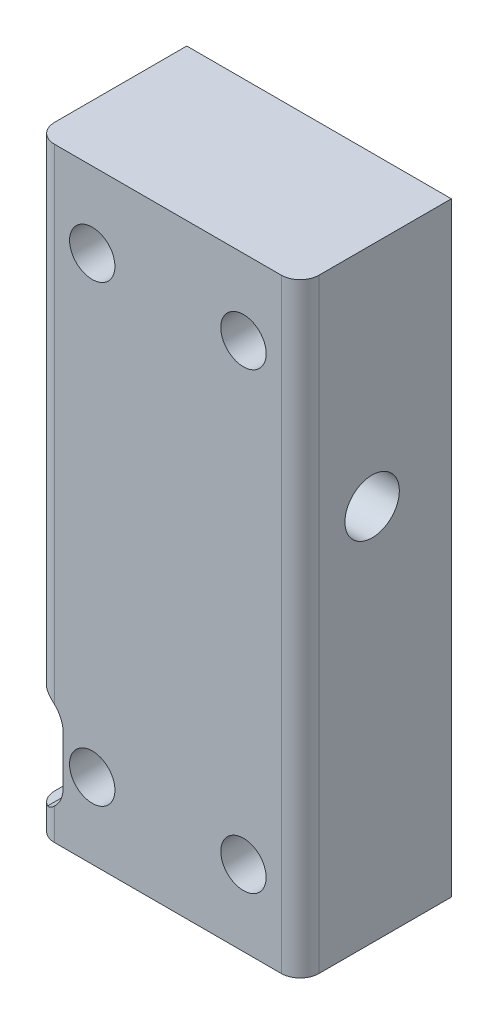
SolidWorks part; units mm, degrees
ref_plane "Front Plane" through (0, 0, 0) normal (0, 0, 1) x (1, 0, 0)
ref_plane "Top Plane" through (0, 0, 0) normal (0, 1, 0) x (1, 0, 0)
ref_plane "Right Plane" through (0, 0, 0) normal (1, 0, 0) x (0, 0, -1)
sketch "Sketch1" plane through (0, 0, 0) normal (0, 1, 0) x (1, 0, 0)
  line L1 (0, 0) -> (22.225, 0)
  line L2 (0, 0) -> (0, 12.7)
  line L3 (0, 12.7) -> (22.225, 12.7)
  line L4 (22.225, 0) -> (22.225, 12.7)
  dimension "D1" = 12.7
  dimension "D2" = 22.225
extrude "Boss-Extrude1" add sketch "Sketch1" along normal blind 50.8
sketch "Sketch2" plane through (0, 0, -12.7) normal (0, 0, -1) x (-1, 0, 0)
  line L0 (-22.225, 50.8) -> (0, 50.8) construction
  line L1 (-22.225, 0) -> (0, 0) construction
  circle A0 centre (-17.4625, 44.45) radius 1.905
  circle A1 centre (-17.4625, 6.35) radius 1.905
  circle A2 centre (-4.7625, 44.45) radius 1.905
  circle A3 centre (-4.7625, 6.35) radius 1.905
  point P6 (-11.1125, 50.8)
  point P13 (0, 0)
  point P14 (0, 0)
  point P15 (0, 0)
  dimension "D4" = 3.81
  dimension "D1" = 6.35
  dimension "D2" = 44.45
  dimension "D3" = 6.35
  dimension "D5" = 6.35
extrude "Cut-Extrude1" cut sketch "Sketch2" against normal through all
ref_plane "Plane1" through (0, 0, -6.35) normal (0, 0, -1) x (-1, 0, 0)
sketch "Sketch3" plane through (0, 0, -6.35) normal (0, 0, -1) x (-1, 0, 0)
  line L0 (0, 10.541) -> (0, 2.159)
  line L1 (0, 50.8) -> (0, 0) construction
  line L2 (0, 2.159) -> (-0.7937, 2.159)
  line L3 (0, 10.541) -> (-0.7937, 10.541)
  line L4 (-2.286, 8.7313) -> (-2.286, 3.9687)
  line L5 (-22.225, 50.8) -> (0, 50.8) construction
  arc A0 (-2.286, 8.7313) -> (-0.7937, 10.541) centre (0, 8.3664) cw
  arc A1 (-0.7937, 2.159) -> (-2.286, 3.9687) centre (0, 4.3336) cw
  point P11 (-2.286, 6.35)
  point P12 (-1.1591, 48.514)
  point P14 (0, 6.35)
  point P15 (-0.7996, 40.386)
  point P16 (-1.2572, 47.635)
  point P17 (0, 0)
  point P18 (-1.1249, 41.6543)
  point P19 (-0.5789, 42.0688)
  point P20 (-1.2859, 40.386)
  point P21 (-0.5911, 46.8313)
  point P22 (-0.5911, 42.0688)
  dimension "D1" = 8.382
  dimension "D2" = 44.45
  dimension "D3" = 4.7625
  dimension "D4" = 2.286
  dimension "D5" = 0.7937
extrude "Cut-Extrude2" cut sketch "Sketch3" against normal through all
sketch "Sketch5" plane through (0, 0, -6.35) normal (0, 0, -1) x (-1, 0, 0)
  line L0 (-2.286, 6.35) -> (0, 6.35) construction
  line L1 (0, 6.35) -> (-2.286, 6.35)
  line L2 (-22.225, 0) -> (0, 0) construction
  line L4 (0, 10.541) -> (-0.7938, 10.541)
  line L5 (0, 2.159) -> (0, 10.541)
  line L6 (-0.7937, 2.159) -> (0, 2.159)
  line L7 (-2.286, 8.7313) -> (-2.286, 3.9687)
  line L8 (0, 10.541) -> (-0.7938, 10.541)
  line L9 (0, 6.35) -> (0, 10.541)
  line L11 (-2.286, 8.7313) -> (-2.286, 6.35)
  arc A3 (-2.286, 3.9687) -> (-0.7937, 2.159) centre (0, 4.3336) ccw
  arc A4 (-0.7938, 10.541) -> (-2.286, 8.7313) centre (0, 8.3664) ccw
  arc A6 (-0.7938, 10.541) -> (-2.286, 8.7313) centre (0, 8.3664) ccw
  dimension "D2" = 6.35
  dimension "D1" = 0
revolve "Cut-Revolve2" cut sketch "Sketch5" angle 360 about L0
fillet "Fillet1" radius 1.5875 3 edges at (0, 30.6705, 0) (0, 1.0795, 0) (22.225, 25.4, 0)
sketch "Sketch6" plane through (22.225, 0, 0) normal (1, 0, 0) x (0, 0, -1)
  circle A0 centre (6.0452, 31.75) radius 2.286
  circle A1 centre (6.0452, 31.75) radius 1.905 construction
  point P2 (0, 0)
  dimension "D1" = 4.572
extrude "Cut-Extrude3" cut sketch "Sketch6" against normal through all
